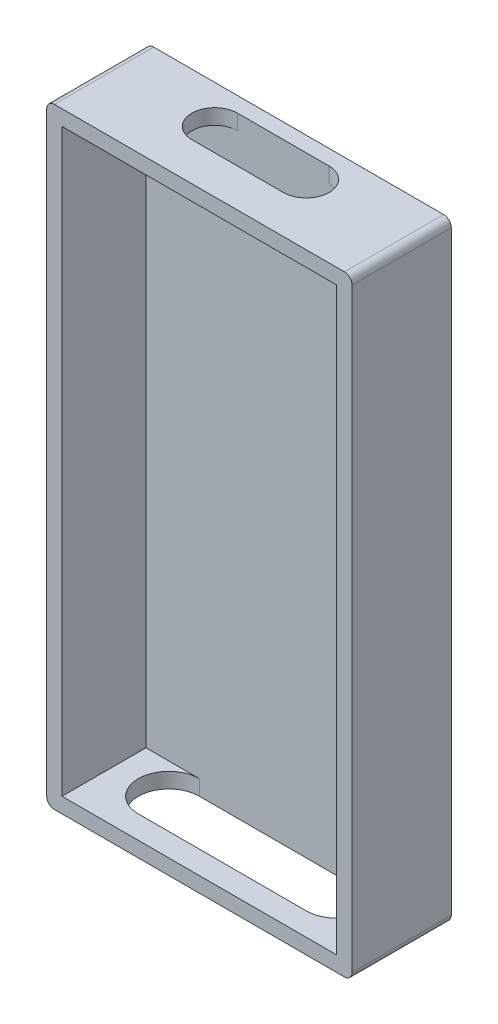
SolidWorks part; units mm, degrees
ref_plane "Front Plane" through (0, 0, 0) normal (0, 0, 1) x (1, 0, 0)
ref_plane "Top Plane" through (0, 0, 0) normal (0, 1, 0) x (1, 0, 0)
ref_plane "Right Plane" through (0, 0, 0) normal (1, 0, 0) x (0, 0, -1)
sketch "Sketch2" plane through (0, 0, 0) normal (0, 0, 1) x (1, 0, 0)
  line L1 (-10, -20) -> (10, -20)
  line L2 (-10, -20) -> (-10, 20)
  line L3 (-10, 20) -> (10, 20)
  line L4 (10, -20) -> (10, 20)
  line L5 (-10, -20) -> (10, 20) construction
  line L6 (-10, 20) -> (10, -20) construction
  point P0 (0, 0)
  dimension "D1" = 40
  dimension "D2" = 20
extrude "Boss-Extrude1" add sketch "Sketch2" along normal blind 6.5
sketch "Sketch4" plane through (0, 0, 6.5) normal (0, 0, 1) x (1, 0, 0)
  line L0 (-10, 20) -> (-10, -20) construction
  line L5 (10, -20) -> (10, 20) construction
  line L6 (-9, 19) -> (8.9971, 19)
  line L8 (-9, 19) -> (-9, -19)
  line L9 (10, 20) -> (-10, 20) construction
  line L19 (-9, -19) -> (8.9971, -19)
  line L20 (8.9971, 19) -> (8.9971, -19)
  line L21 (-10, -20) -> (10, -20) construction
  dimension "D1" = 1.0029
  dimension "D2" = 1
  dimension "D3" = 1
  dimension "D4" = 1
extrude "Cut-Extrude1" cut sketch "Sketch4" against normal offset from surface (5.5 mm away) 1 up to face at (0, 0, 0)
sketch "Sketch6" plane through (0, -20, 0) normal (0, -1, 0) x (1, 0, 0)
  line L0 (-5.5, 3) -> (5.5, 3) construction
  line L1 (-5.5, 5) -> (5.5, 5)
  line L2 (-5.5, 1) -> (5.5, 1)
  line L3 (-10, 0) -> (10, 0) construction
  line L4 (0, 6.5) -> (0, 0) construction
  line L5 (-10, 6.5) -> (10, 6.5) construction
  arc A0 (-5.5, 5) -> (-5.5, 1) centre (-5.5, 3) ccw
  arc A1 (5.5, 1) -> (5.5, 5) centre (5.5, 3) ccw
  point P2 (0, 3)
  dimension "D1" = 4
  dimension "D2" = 11
  dimension "D3" = 1
extrude "Cut-Extrude4" cut sketch "Sketch6" against normal up to surface (1 mm away) up to face at (-0.0014, -19, 3.75)
sketch "Sketch8" plane through (0, 20, 0) normal (0, 1, 0) x (1, 0, 0)
  line L0 (-3, -2.5) -> (3, -2.5) construction
  line L1 (-3, -1) -> (3, -1)
  line L2 (-3, -4) -> (3, -4)
  line L3 (10, -6.5) -> (-10, -6.5) construction
  line L4 (0, 0) -> (0, -6.5) construction
  line L5 (10, 0) -> (-10, 0) construction
  arc A0 (-3, -1) -> (-3, -4) centre (-3, -2.5) ccw
  arc A1 (3, -4) -> (3, -1) centre (3, -2.5) ccw
  point P2 (0, -2.5)
  dimension "D2" = 1.5
  dimension "D1" = 6
  dimension "D3" = 1
extrude "Cut-Extrude5" cut sketch "Sketch8" against normal up to surface (1 mm away) up to face at (-0.0014, 19, 3.75)
fillet "Fillet1" radius 0.5 4 edges at (10, 20, 3.25) (-10, 20, 3.25) (-10, -20, 3.25) (10, -20, 3.25)
